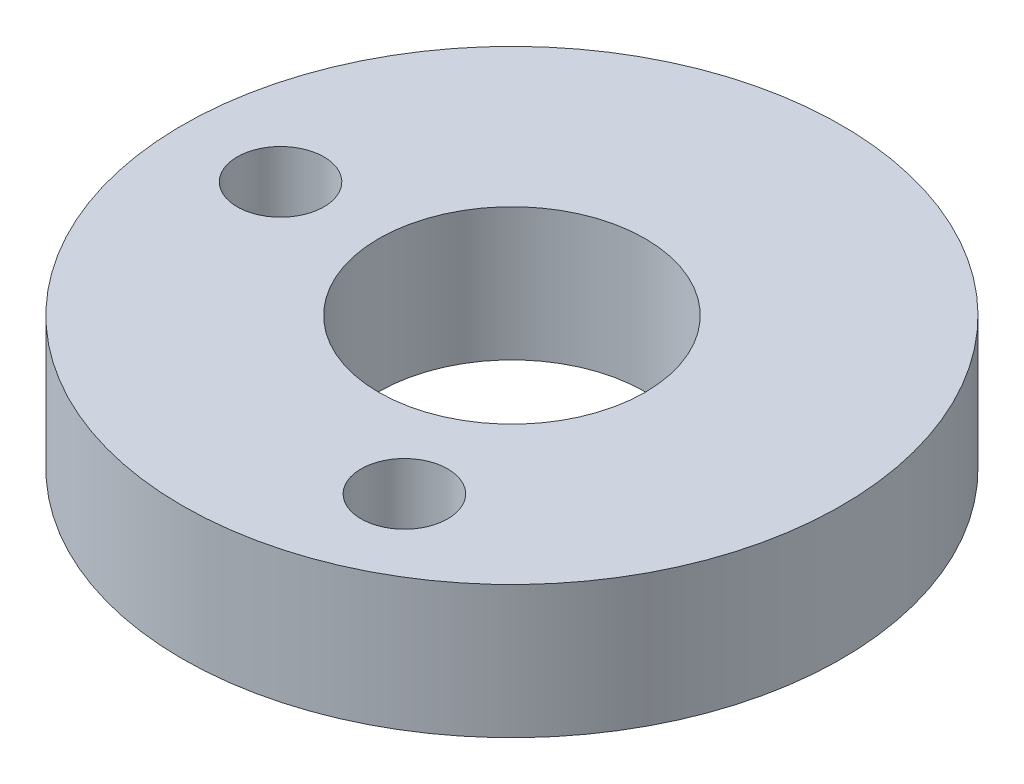
SolidWorks part; units mm, degrees
ref_plane "Front Plane" through (0, 0, 0) normal (0, 0, 1) x (1, 0, 0)
ref_plane "Top Plane" through (0, 0, 0) normal (0, 1, 0) x (1, 0, 0)
ref_plane "Right Plane" through (0, 0, 0) normal (1, 0, 0) x (0, 0, -1)
sketch "Sketch1" plane through (0, 0, 0) normal (0, 1, 0) x (1, 0, 0)
  circle A0 centre (0, 0) radius 31.55
  circle A1 centre (0, 0) radius 12.75
  dimension "D1" = 63.1
  dimension "D2" = 25.5
extrude "Boss-Extrude1" add sketch "Sketch1" along normal blind 12.7
sketch "Sketch2" plane through (0, 0, 0) normal (0, -1, 0) x (1, 0, 0)
  line L0 (-12.75, 0) -> (-31.55, 0) construction
  line L1 (6.985, 0) -> (-6.985, 0) construction
  line L2 (-22.15, 0) -> (9.6446, 19.94) construction
  circle A0 centre (0, 0) radius 12.75 construction
  circle A1 centre (0, 0) radius 31.55 construction
  circle A2 centre (-22.15, 0) radius 4.15
  circle A4 centre (9.6446, 19.94) radius 4.15
  point P12 (5.7083, 24.8681)
  dimension "D1" = 8.3
  dimension "D2" = 22.15
  dimension "D3" = 8.3
  dimension "D5" = 22.15
  dimension "D4" = 37.53
extrude "Cut-Extrude1" cut sketch "Sketch2" against normal blind 12.7
